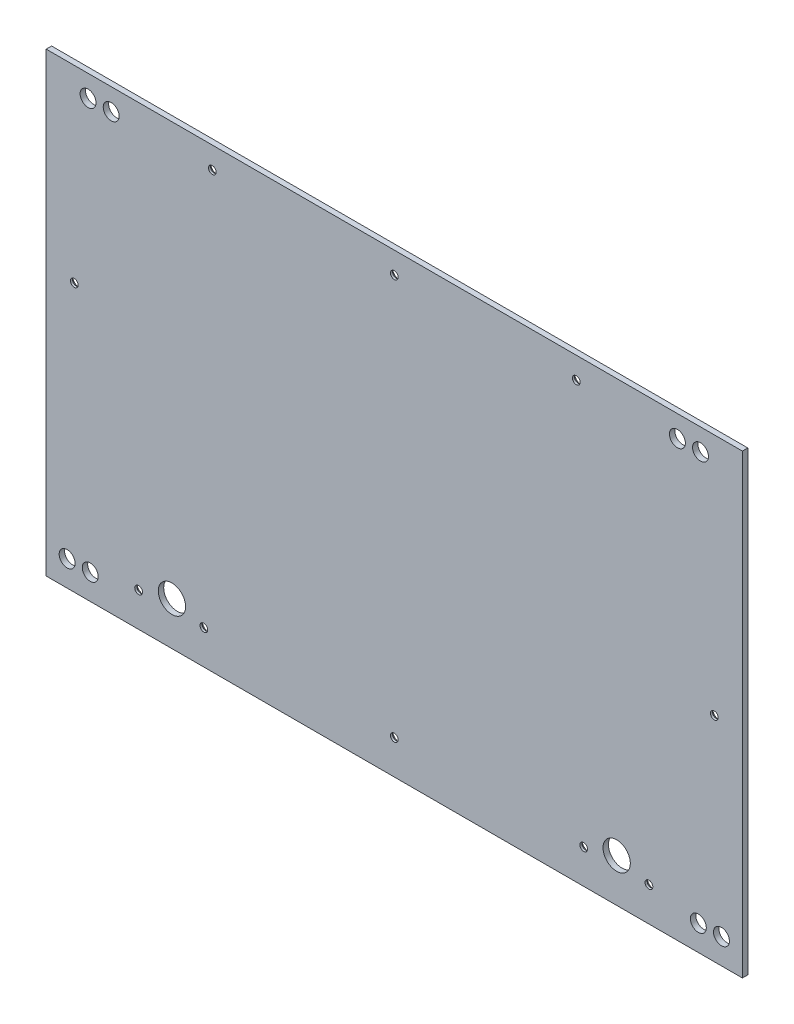
SolidWorks part; units mm, degrees
material "ABS"
ref_plane "X-Y Datum" through (0, 0, 0) normal (0, 0, 1) x (1, 0, 0)
ref_plane "X-Z Datum" through (0, 0, 0) normal (0, 1, 0) x (1, 0, 0)
ref_plane "Y-Z Datum" through (0, 0, 0) normal (1, 0, 0) x (0, 0, -1)
sketch "Sketch1" plane through (0, 0, 0) normal (0, 0, 1) x (1, 0, 0)
  line L0 (-153.025, 98.7125) -> (-153.025, -98.7125)
  line L1 (-153.025, 98.7125) -> (153.025, 98.7125)
  line L2 (-153.025, 98.7125) -> (-153.025, -98.7125)
  line L3 (-153.025, -98.7125) -> (153.025, -98.7125)
  line L4 (153.025, 98.7125) -> (153.025, -98.7125)
  line L5 (-153.025, 98.7125) -> (153.025, -98.7125) construction
  line L6 (-153.025, -98.7125) -> (153.025, 98.7125) construction
  line L7 (-153.025, -98.7125) -> (153.025, -98.7125)
  line L8 (153.025, 98.7125) -> (153.025, -98.7125)
  line L9 (-153.025, 98.7125) -> (153.025, 98.7125)
  circle A0 centre (-142.25, -87.9375) radius 10.775
  circle A1 centre (-118.25, -87.9375) radius 10.775 construction
  circle A2 centre (-130.25, -64.9375) radius 10.775
  point P0 (0, 0)
  dimension "D1" = 21.55
  dimension "D2" = 24
  dimension "D3" = 23
  dimension "D4" = 12
  dimension "D5" = 197.425
  dimension "D6" = 306.05
  dimension "D7" = 0
extrude "Boss-Extrude1" add sketch "Sketch1" along normal blind 2.3813 contours A0 L3 L4 L1 L2 A2 | A2 | A0 | A0 L2 L3 | L9 L0 L7 L8 L1 L4 L3 L2
sketch "Sketch9" plane through (0, 98.7125, 0) normal (0, 1, 0) x (1, 0, 0)
  line L4 (153.025, 0) -> (-153.025, 0)
  line L5 (-153.025, 0) -> (-153.025, -2.3813)
  line L6 (-153.025, -2.3813) -> (153.025, -2.3813)
  line L7 (153.025, -2.3813) -> (153.025, 0)
  line L8 (153.025, 0) -> (-153.025, 0)
  line L9 (-153.025, 0) -> (-153.025, -2.3813)
  line L10 (-153.025, -2.3813) -> (153.025, -2.3813)
  line L11 (153.025, -2.3813) -> (153.025, 0)
  dimension "D1" = 0
extrude "Boss-Extrude2" add sketch "Sketch9" along normal blind 3.175
sketch "Sketch10" plane through (0, 0, 0) normal (0, 0, -1) x (-1, 0, 0)
  circle A0 centre (-134.61, 92.3625) radius 3.5
  circle A1 centre (-124.45, 92.3625) radius 3.5
  circle A2 centre (-143.8175, -87.5375) radius 3.5
  circle A3 centre (-133.6575, -87.5375) radius 3.5
  point P0 (-143.8175, -87.5375)
  point P1 (-133.6575, -87.5375)
  point P3 (-134.61, 92.3625)
  point P5 (-124.45, 92.3625)
  dimension "D1" = 7
extrude "Cut-Extrude1" cut sketch "Sketch10" against normal through all
mirror "Mirror1" about plane through (0, 0, 0) normal (1, 0, 0) of "Cut-Extrude1"
sketch "Sketch11" plane through (0, 0, 0) normal (0, 0, -1) x (-1, 0, 0)
  point P0 (-111.94, -83.7125)
  point P1 (-83.25, -83.7125)
  point P3 (-140.6875, -4.9375)
  point P5 (-80, 92.3625)
  point P7 (0, 92.3625)
  point P9 (80, 92.3625)
  point P11 (140.6875, 19.0625)
  point P13 (112.402, -83.7125)
  point P15 (83.712, -83.7125)
  point P17 (0, -83.7125)
hole_wizard "CSK for M3 Flat Head Machine Screw1" positions "Sketch11" profile "Sketch12" countersink size "M3" standard "ANSI Metric" end condition through all
sketch "Sketch12" plane through (111.94, -83.7125, 0) normal (1, 0, 0) x (0, 1, 0)
  line L0 (0, 0) -> (0, 2.3812)
  line L1 (0, 2.3812) -> (1.7, 2.3812)
  line L2 (1.7, 2.3812) -> (1.7, 1.45)
  line L3 (1.7, 1.45) -> (3.15, 0)
  line L5 (3.15, 0) -> (0, 0)
  line L6 (-1.7, 1.45) -> (-3.15, 0) construction
  line L11 (0, -6.35) -> (0, 107.95) construction
  dimension "Thru Hole Dia." = 3.4
  dimension "Thru Hole Depth" = 2.3813
  dimension "Near C'Sink Dia." = 6.3
  dimension "Near C'Sink Angle" = 90
sketch "Sketch13" plane through (0, 0, 0) normal (0, 0, -1) x (-1, 0, 0)
  circle A0 centre (-97.75, -79.7125) radius 6 construction
  circle A1 centre (97.75, -79.7125) radius 6 construction
  circle A2 centre (-97.75, -79.7125) radius 6
  circle A3 centre (97.75, -79.7125) radius 6
extrude "Cut-Extrude2" cut sketch "Sketch13" against normal through all
